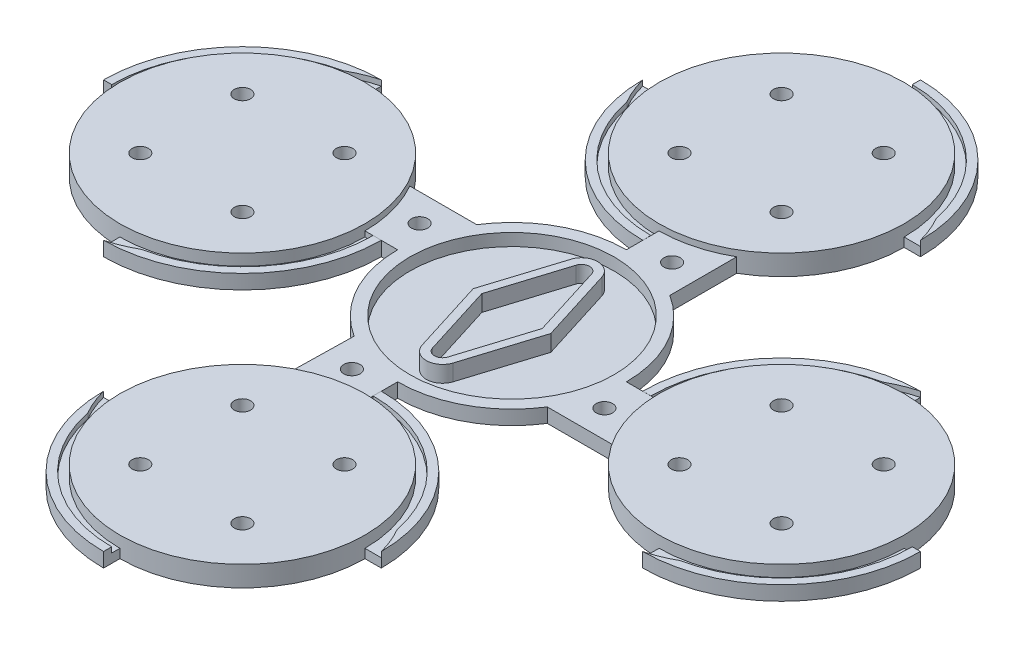
SolidWorks part; units mm, degrees
ref_plane "前视基准面" through (0, 0, 0) normal (0, 0, 1) x (1, 0, 0)
ref_plane "上视基准面" through (0, 0, 0) normal (0, 1, 0) x (1, 0, 0)
ref_plane "右视基准面" through (0, 0, 0) normal (1, 0, 0) x (0, 0, -1)
sketch "草图1" plane through (0, 0, 0) normal (0, 1, 0) x (1, 0, 0)
  circle A0 centre (0, 0) radius 30
extrude "凸台-拉伸1" add sketch "草图1" along normal blind 11
sketch "草图3" plane through (0, 0, 0) normal (0, -1, 0) x (1, 0, 0)
  line L0 (-34, 0) -> (-30, 0)
  line L1 (0, -34) -> (0, -30)
  line L3 (0, 34) -> (0, 30)
  line L4 (34, 0) -> (30, 0)
  arc A0 (-34, 0) -> (0, -34) centre (0, 0) ccw
  circle A1 centre (0, 0) radius 30 construction
  arc A2 (-30, 0) -> (0, -30) centre (0, 0) ccw
  arc A3 (0, 34) -> (34, 0) centre (0, 0) cw
  arc A4 (0, 30) -> (30, 0) centre (0, 0) cw
  dimension "D1" = 34
extrude "凸台-拉伸2" add sketch "草图3" against normal blind 4
ref_axis "基准轴1" through (0, 0, 0) along (0, 1, 0)
sketch "草图6" plane through (0, 0, 0) normal (0, 0, -1) x (-1, 0, 0)
  line L1 (-30, 2.2) -> (-32, 2.2)
  line L2 (-32, 2.2) -> (-32, 3.52)
  line L3 (-32, 3.52) -> (-34, 3.52)
  line L4 (-34, 4) -> (-34, 0) construction
  line L5 (-34, 3.52) -> (-34, 4)
  line L6 (-34, 4) -> (-30, 4)
  line L7 (-30, 4) -> (-30, 2.2)
  dimension "D1" = 3.52
  dimension "D2" = 2
  dimension "D3" = 1.32
revolve "切除-旋转8" cut sketch "草图6" angle 360 about axis through (0, 0, 0) along (0, 1, 0)
sketch "草图7" plane through (0, 3.52, 0) normal (0, 1, 0) x (1, 0, 0)
  line L0 (6.5224, -31.3282) -> (-2.1919, -31.4445)
  line L1 (-2.1919, -31.4445) -> (0, -34)
  line L2 (-6.5224, 31.3282) -> (2.581, 31.0313)
  line L3 (2.581, 31.0313) -> (0, 34)
  arc A0 (0, 34) -> (-6.5224, 31.3282) centre (6.8858, 7.8928) ccw
  arc A1 (0, 32) -> (-32, 0) centre (0, 0) ccw construction
  arc A2 (0, -34) -> (6.5224, -31.3282) centre (-6.8858, -7.8928) ccw
  arc A3 (0, -32) -> (32, 0) centre (0, 0) ccw construction
extrude "切除-拉伸1" cut sketch "草图7" against normal blind 1.32
sketch "草图8" plane through (0, 11, 0) normal (0, 1, 0) x (1, 0, 0)
  line L0 (-30, 0) -> (-30, 30)
  line L1 (-30, 30) -> (30, 30)
  line L2 (30, 30) -> (30, -30)
  line L3 (30, -30) -> (-30, -30)
  line L4 (-30, -30) -> (-30, 0)
  line L5 (-30, 0) -> (-12.5, 0)
  line L6 (-2.7365, 12.5) -> (-30, 12.5)
  line L7 (-2.7365, 30) -> (-2.7365, 12.5)
  line L8 (-12.5, 0) -> (-12.5, 30)
  line L9 (-12.5, 0) -> (-12.5, -30)
  line L10 (0, -30) -> (0, -12.5)
  line L11 (-30, -12.5) -> (30, -12.5)
  line L12 (30, 0) -> (12.5, 0)
  line L13 (12.5, 30) -> (12.5, -30)
  circle A1 centre (-12.5, 12.5) radius 2
  circle A2 centre (-12.5, -12.5) radius 2
  circle A3 centre (12.5, 12.5) radius 2
  circle A4 centre (12.5, -12.5) radius 2
  dimension "D3" = 17.5
  dimension "D4" = 17.5
  dimension "D5" = 4
  dimension "D6" = 4
  dimension "D7" = 4
  dimension "D8" = 4
  dimension "D1" = 17.5
  dimension "D2" = 17.5
extrude "切除-拉伸2" cut sketch "草图8" against normal through all contours L13 A3 | L13 A3 | L11 A2 L9 | L9 A2 L11 | L11 A2 L9 | L9 A2 L11 | A4 | A1
chamfer "倒角2" distance 2 angle 45 4 edges at (-12.5, 11, 14.5) (12.5, 11, 14.5) (12.5, 11, -10.5) (-12.5, 11, -10.5)
sketch "草图11" plane through (0, 0, 0) normal (0, 1, 0) x (1, 0, 0)
  line L0 (-34, 0) -> (38, 0)
  line L1 (66, 0) -> (66, 36)
  line L2 (0, 0) -> (38, 0)
  line L3 (66, 0) -> (102, 0)
  line L4 (25.9808, 15) -> (42.3568, 15)
  line L5 (66, 0) -> (66, -36)
  line L9 (81, 40.0192) -> (81, 23.6432)
  line L10 (66, 100) -> (66, 28)
  line L11 (106.0192, -15) -> (89.6432, -15)
  line L12 (166, 0) -> (94, 0)
  line L13 (51, -40.0192) -> (51, -23.6432)
  line L14 (66, -100) -> (66, -28)
  circle A0 centre (0, 0) radius 30 construction
  arc A1 (30, 0) -> (29.0474, 7.5) centre (0, 0) ccw
  arc A2 (38, 0) -> (42.3568, 15) centre (66, 0) ccw
  circle A3 centre (66, 0) radius 25
  arc A4 (66, 36) -> (73.5, 36.9526) centre (66, 66) ccw
  arc A5 (102, 0) -> (102.9526, -7.5) centre (132, 0) ccw
  arc A6 (66, -36) -> (58.5, -36.9526) centre (66, -66) ccw
  arc A7 (30, 0) -> (25.9808, 15) centre (0, 0) ccw
  arc A8 (66, 36) -> (81, 40.0192) centre (66, 66) ccw
  arc A9 (102, 0) -> (106.0192, -15) centre (132, 0) ccw
  arc A10 (66, -36) -> (51, -40.0192) centre (66, -66) ccw
  dimension "D2" = 36
  dimension "D1" = 100
  dimension "D3" = 36
  dimension "D4" = 36
  dimension "D6" = 4
  dimension "D5" = 4
extrude "凸台-拉伸4" add sketch "草图11" along normal blind 3.5
sketch "草图12" plane through (0, 0, 0) normal (0, -1, 0) x (1, 0, 0)
  circle A0 centre (66, 0) radius 25
extrude "凸台-拉伸5" add sketch "草图12" against normal blind 0.5
sketch "草图13" plane through (0, 0.5, 0) normal (0, 1, 0) x (1, 0, 0)
  line L0 (58.6, 0) -> (64.1105, -17.5919)
  line L1 (58.6, 0) -> (64.1105, 17.5919)
  line L2 (73.4, 0) -> (67.8895, 17.5919)
  line L3 (73.4, 0) -> (67.8895, -17.5919)
  line L4 (56.5, 0) -> (62.2022, -18.1905)
  line L5 (56.5, 0) -> (62.3401, 18.5638)
  line L6 (75.5, 0) -> (69.7978, 18.1905)
  line L7 (75.5, 0) -> (69.7978, -18.1905)
  arc A0 (67.8895, 17.5919) -> (64.1105, 17.5919) centre (66, 17) ccw
  arc A1 (64.1105, -17.5919) -> (67.8895, -17.5919) centre (66, -17) ccw
  arc A3 (62.2022, -18.1905) -> (69.7978, -18.1905) centre (66, -17) ccw
  circle A4 centre (66, 0) radius 25 construction
  arc A6 (69.7978, 18.1905) -> (62.104, 17.8132) centre (66, 17) ccw
  point P3 (66, 0)
  point P16 (66, 0)
  dimension "D1" = 14.8
  dimension "D2" = 19
  dimension "D3" = 0
extrude "凸台-拉伸7" add sketch "草图13" along normal blind 4 contours L6 A6 L5 L4 A3 L7 A1 L0 L1 A0 L2 L3
pattern_circular "阵列(圆周)1" count 4 over 360 about axis through (66, 0, 0) along (0, 1, 0) of "倒角2", "切除-拉伸1", "切除-拉伸2", "切除-旋转8", "凸台-拉伸2", "凸台-拉伸1"
sketch "草图14" plane through (0, 0, 0) normal (0, 0, 1) x (1, 0, 0)
  line L7 (-30, 11) -> (-30, 5)
  line L8 (-30, 11) -> (-30, 2.2) construction
  line L9 (-30, 5) -> (176.9757, 5)
  line L10 (176.9757, 5) -> (176.9757, 23.5393)
  line L11 (176.9757, 23.5393) -> (-30, 23.5393)
  line L12 (-30, 23.5393) -> (-30, 11)
  dimension "D1" = 6
extrude "切除-拉伸3" cut sketch "草图14" against normal through all both and the other way through all
sketch "草图15" plane through (0, 3.5, 0) normal (0, 1, 0) x (1, 0, 0)
  line L0 (66, 34) -> (66, 37.3031)
  line L1 (66, 37.3031) -> (66, 66)
  line L2 (66, 66) -> (76.0072, 45.0666)
  line L3 (76.0072, 45.0666) -> (81, 42.2028)
  line L4 (81, 42.2028) -> (81, 37.7334)
  line L5 (81, 37.7334) -> (81, 32.5358)
  line L6 (81, 37.7334) -> (81, 23.6432) construction
  line L7 (81, 32.5358) -> (66, 34)
  line L8 (103.7334, -15) -> (111.3488, -15)
  line L9 (103.7334, -15) -> (89.6432, -15) construction
  line L10 (111.3488, -15) -> (111.3488, 0)
  line L11 (111.3488, 0) -> (100, 0)
  line L12 (100, 0) -> (100, -15)
  line L13 (100, -15) -> (103.7334, -15)
  line L14 (66, -28) -> (66, -39.1763)
  line L15 (66, -39.1763) -> (50.6424, -42.2172)
  line L16 (50.6424, -42.2172) -> (51, -23.6432)
  line L17 (51, -23.6432) -> (66, -28)
  arc A0 (66, 34) -> (81, 37.7334) centre (66, 66) ccw construction
  arc A1 (34.6718, 59.4776) -> (81, 37.7334) centre (66, 66) ccw construction
extrude "凸台-拉伸8" add sketch "草图15" against normal blind 2
sketch "草图17" plane through (0, 3.5, 0) normal (0, 1, 0) x (1, 0, 0)
  line L0 (66, 0) -> (34, 0)
  line L1 (66, 0) -> (66, 32)
  line L2 (66, 0) -> (35.0904, 8.2822)
  circle A0 centre (66, 0) radius 32
  circle A1 centre (35.0904, 8.2822) radius 2
  circle A2 centre (74.2822, 30.9096) radius 2
  circle A3 centre (96.9096, -8.2822) radius 2
  circle A4 centre (57.7178, -30.9096) radius 2
  dimension "D1" = 15
  dimension "D2" = 4
  dimension "D3" = 4
extrude "切除-拉伸4" cut sketch "草图17" against normal through all both and the other way through all contours A1 | A2 | A3 | A4
